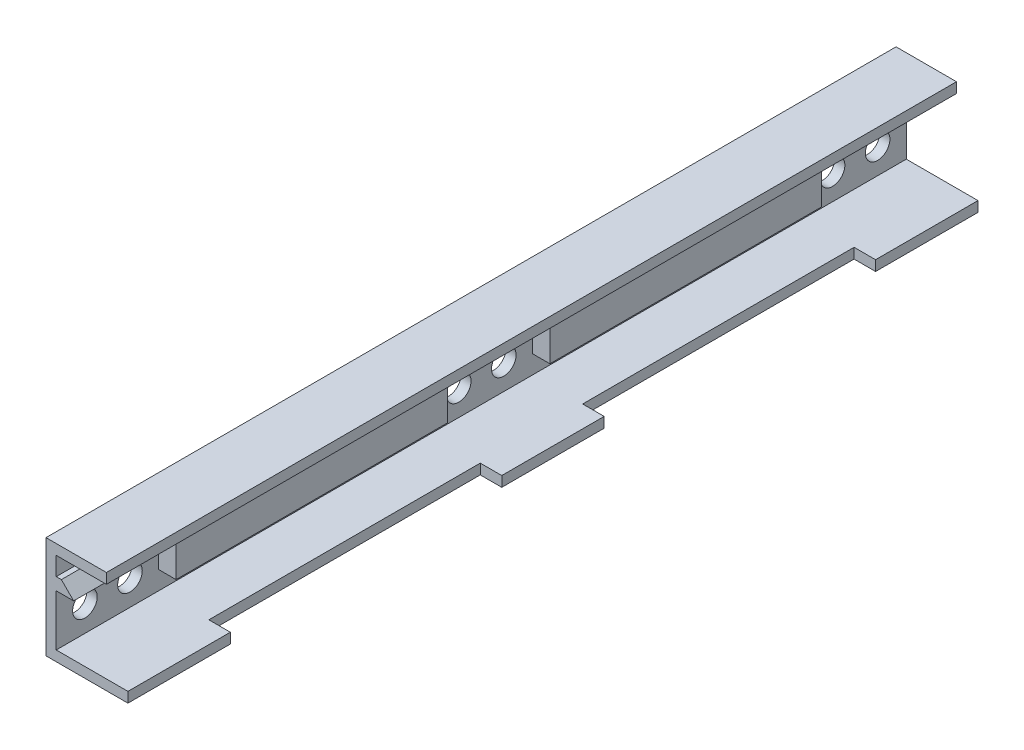
SolidWorks part; units mm, degrees
ref_plane "Front Plane" through (0, 0, 0) normal (0, 0, 1) x (1, 0, 0)
ref_plane "Top Plane" through (0, 0, 0) normal (0, 1, 0) x (1, 0, 0)
ref_plane "Right Plane" through (0, 0, 0) normal (1, 0, 0) x (0, 0, -1)
sketch "Sketch2" plane through (0, 0, 0) normal (0, 0, 1) x (1, 0, 0)
  line L0 (0, 0) -> (8, 0)
  line L1 (8, 0) -> (8, 1)
  line L2 (8, 1) -> (1, 1)
  line L3 (1, 1) -> (1, 6)
  line L4 (1, 6) -> (2.7, 6)
  line L5 (2.7, 6) -> (1.5, 7.2)
  line L6 (1.5, 7.2) -> (1, 7.2)
  line L7 (1, 7.2) -> (1, 9)
  line L8 (1, 9) -> (5.9, 9)
  line L9 (5.9, 9) -> (5.9, 10)
  line L10 (5.9, 10) -> (0, 10)
  line L11 (0, 10) -> (0, 0)
  point P5 (0, 0)
  point P13 (0, 0)
  point P14 (0, 0)
  dimension "D1" = 8
  dimension "D2" = 7
  dimension "D3" = 1
  dimension "D4" = 1
  dimension "D5" = 4.9
  dimension "D6" = 45
  dimension "D7" = 0.5
  dimension "D8" = 1.8
  dimension "D9" = 5
  dimension "D10" = 1
  dimension "D11" = 8
extrude "Boss-Extrude1" add sketch "Sketch2" along normal blind 10
sketch "Sketch6" plane through (0, 0, 10) normal (0, 0, 1) x (1, 0, 0)
  line L0 (0, 0) -> (5.9, 0)
  line L1 (0, 0) -> (8, 0) construction
  line L2 (1, 1) -> (1, 2.8)
  line L3 (2.7, 6) -> (1.5, 7.2)
  line L4 (1, 1) -> (1, 6) construction
  line L5 (1, 2.8) -> (2.7, 2.8)
  line L6 (2.7, 2.8) -> (2.7, 6)
  line L7 (1, 7.2) -> (1, 9)
  line L8 (1, 9) -> (5.9, 9)
  line L9 (1, 9) -> (5.9, 9) construction
  line L10 (5.9, 9) -> (5.9, 10)
  line L11 (5.9, 10) -> (0, 10) construction
  line L12 (5.9, 10) -> (0, 10)
  line L13 (0, 10) -> (0, 0)
  line L14 (5.9, 0) -> (5.9, 1)
  line L15 (8, 1) -> (1, 1) construction
  line L16 (5.9, 1) -> (1, 1)
  line L17 (1.5, 7.2) -> (1, 7.2)
  dimension "D1" = 5.9
  dimension "D2" = 5.9
  dimension "D3" = 1.8
extrude "Boss-Extrude2" add sketch "Sketch6" along normal blind 26.5
sketch "Sketch8" plane through (0, 0, 36.5) normal (0, 0, 1) x (1, 0, 0)
  line L0 (0, 0) -> (8, 0)
  line L1 (0, 0) -> (0, 10)
  line L2 (0, 10) -> (5.9, 10)
  line L3 (1, 1) -> (8, 1)
  line L4 (8, 1) -> (8, 0)
  line L5 (5.9, 9) -> (1, 9)
  line L6 (1, 9) -> (1, 7.2)
  line L7 (1, 7.2) -> (1.5, 7.2)
  line L8 (1.5, 7.2) -> (2.7, 6)
  line L9 (2.7, 6) -> (1, 6)
  line L10 (1, 6) -> (1, 1)
  line L11 (5.9, 10) -> (5.9, 9)
  dimension "D1" = 8
  dimension "D2" = 4.9
extrude "Boss-Extrude3" add sketch "Sketch8" along normal blind 10
sketch "Sketch9" plane through (0, 0, 46.5) normal (0, 0, 1) x (1, 0, 0)
  line L0 (0, 0) -> (5.9, 0)
  line L1 (0, 0) -> (8, 0) construction
  line L2 (5.9, 0) -> (5.9, 1)
  line L3 (8, 1) -> (1, 1) construction
  line L4 (5.9, 1) -> (1, 1)
  line L5 (1, 1) -> (1, 2.8)
  line L6 (1, 1) -> (1, 6) construction
  line L7 (0, 0) -> (0, 10)
  line L8 (0, 10) -> (5.9, 10)
  line L9 (5.9, 10) -> (0, 10) construction
  line L10 (5.9, 10) -> (5.9, 9)
  line L11 (1, 9) -> (5.9, 9) construction
  line L12 (5.9, 9) -> (1, 9)
  line L13 (1, 9) -> (1, 7.2)
  line L14 (1, 7.2) -> (1.5, 7.2)
  line L15 (1.5, 7.2) -> (2.7, 6)
  line L16 (2.7, 6) -> (2.7, 2.8)
  line L17 (2.7, 2.8) -> (1, 2.8)
  dimension "D1" = 5.9
  dimension "D2" = 5.9
  dimension "D3" = 1.8
extrude "Boss-Extrude4" add sketch "Sketch9" along normal blind 26.5
sketch "Sketch10" plane through (0, 0, 73) normal (0, 0, 1) x (1, 0, 0)
  line L0 (0, 0) -> (8, 0)
  line L1 (1, 1) -> (8, 1)
  line L2 (8, 1) -> (8, 0)
  line L3 (0, 0) -> (0, 10)
  line L4 (0, 10) -> (5.9, 10)
  line L5 (2.7, 6) -> (1.5, 7.2)
  line L6 (1.5, 7.2) -> (1, 7.2)
  line L7 (1, 7.2) -> (1, 9)
  line L8 (1, 9) -> (5.9, 9)
  line L9 (5.9, 9) -> (5.9, 10)
  line L10 (2.7, 6) -> (1, 6)
  line L11 (1, 6) -> (1, 1)
  dimension "D1" = 8
  dimension "D2" = 5.9
extrude "Boss-Extrude5" add sketch "Sketch10" along normal blind 10
hole_wizard "M2 Clearance Hole1" positions "Sketch4" profile "Sketch5" hole size "M2" standard "ANSI Metric" end condition through all
sketch "Sketch4" plane through (1, 0, 0) normal (1, 0, 0) x (0, 0, -1)
  line L0 (-83, 0) -> (0, 0) construction
  line L1 (-83, 0) -> (0, 0) construction
  line L2 (-83, 0) -> (0, 0) construction
  point P0 (-2.8, 3.5)
  point P2 (-7.2, 3.5)
  point P20 (-39.3, 3.5)
  point P22 (-43.7, 3.5)
  point P33 (-75.8, 3.5)
  point P35 (-80.2, 3.5)
  dimension "D1" = 3.5
  dimension "D2" = 2.8
  dimension "D3" = 3.5
  dimension "D4" = 7.2
  dimension "D5" = 39.3
  dimension "D6" = 3.5
  dimension "D7" = 3.5
  dimension "D8" = 43.7
  dimension "D9" = 3.5
  dimension "D10" = 3.5
  dimension "D11" = 75.8
  dimension "D12" = 80.2
sketch "Sketch5" plane through (1, 3.5, 2.8) normal (0, 1, 0) x (0, 0, -1)
  line L0 (0, 0) -> (0, 1)
  line L1 (0, 1) -> (1.2, 1)
  line L2 (1.2, 1) -> (1.2, 0)
  line L5 (1.2, 0) -> (0, 0)
  line L11 (0, -6.35) -> (0, 107.95) construction
  dimension "Thru Hole Dia." = 2.4
  dimension "Thru Hole Depth" = 1
